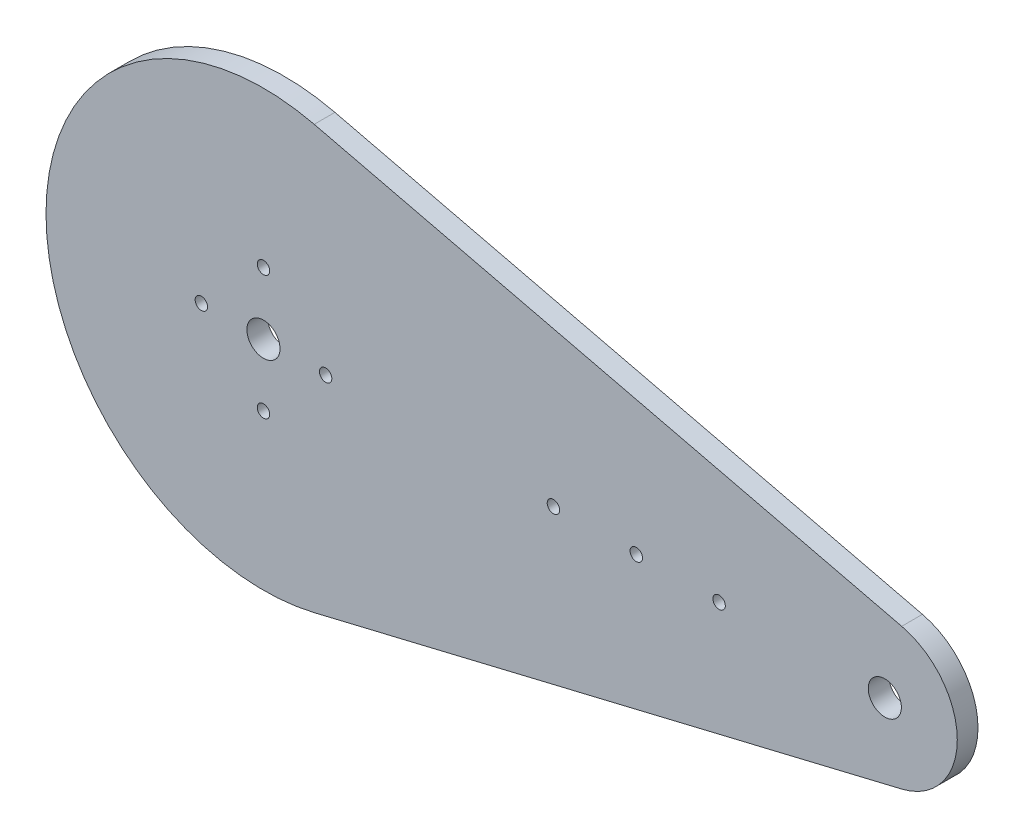
SolidWorks part; units mm, degrees
ref_plane "Front Plane" through (0, 0, 0) normal (0, 0, 1) x (1, 0, 0)
ref_plane "Top Plane" through (0, 0, 0) normal (0, 1, 0) x (1, 0, 0)
ref_plane "Right Plane" through (0, 0, 0) normal (1, 0, 0) x (0, 0, -1)
sketch "Sketch1" plane through (0, 0, 0) normal (0, 0, 1) x (1, 0, 0)
  line L0 (0, 0) -> (150, 0) construction
  line L1 (12.25, 51.0508) -> (154.0833, 17.0169)
  line L2 (12.25, -51.0508) -> (154.0833, -17.0169)
  circle A0 centre (0, 0) radius 52.5
  circle A1 centre (150, 0) radius 17.5
  circle A2 centre (0, 0) radius 4
  circle A3 centre (150, 0) radius 4
  circle A4 centre (0, 0) radius 15 construction
  circle A5 centre (15, 0) radius 1.5
  circle A6 centre (0, 15) radius 1.5
  circle A7 centre (-15, 0) radius 1.5
  circle A8 centre (0, -15) radius 1.5
  circle A9 centre (90, 0) radius 1.5
  circle A10 centre (110, 0) radius 1.5
  circle A11 centre (70, 0) radius 1.5
  point P26 (0, 0)
  dimension "D1" = 105
  dimension "D2" = 35
  dimension "D4" = 8
  dimension "D5" = 8
  dimension "D6" = 30
  dimension "D7" = 3
  dimension "D8" = 3
  dimension "D9" = 3
  dimension "D10" = 3
  dimension "D3" = 150
  dimension "D11" = 20
  dimension "D12" = 20
  dimension "D13" = 60
extrude "Boss-Extrude1" add sketch "Sketch1" along normal blind 5
